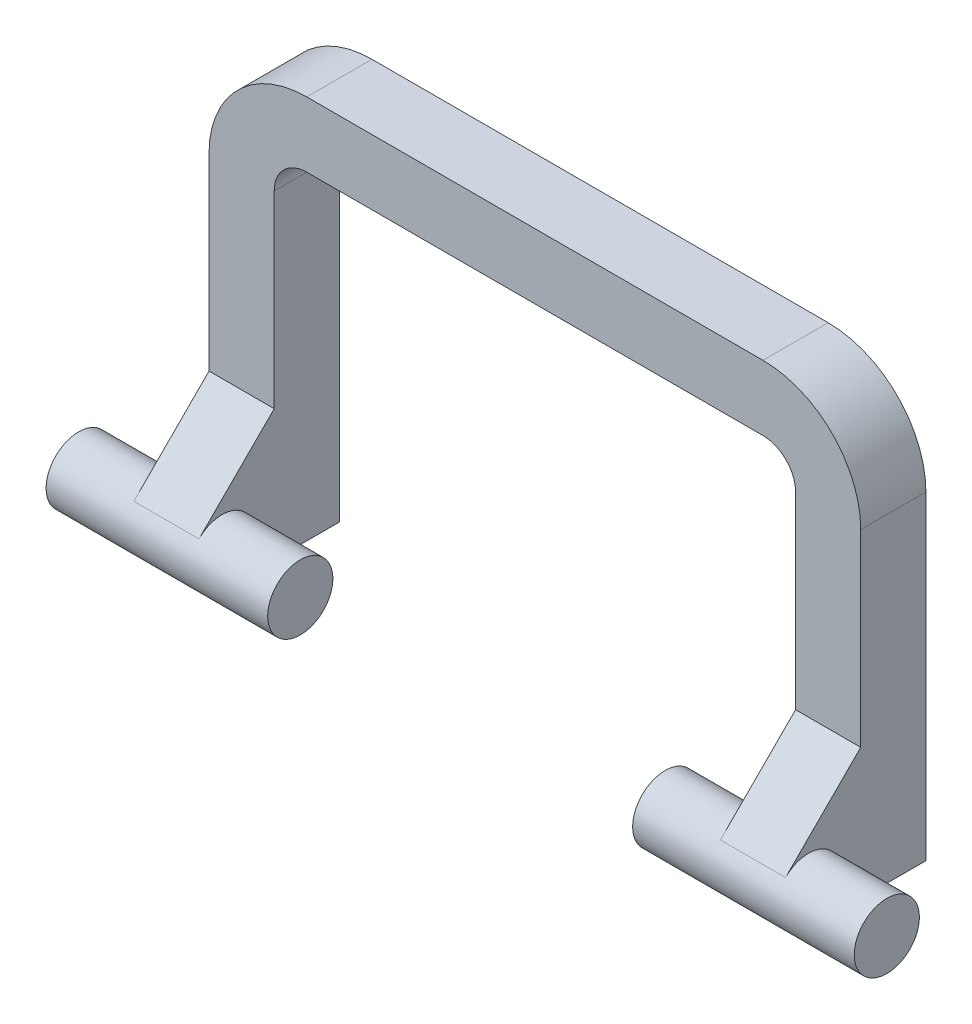
SolidWorks part; units mm, degrees
ref_plane "前视基准面" through (0, 0, 0) normal (0, 0, 1) x (1, 0, 0)
ref_plane "上视基准面" through (0, 0, 0) normal (0, 1, 0) x (1, 0, 0)
ref_plane "右视基准面" through (0, 0, 0) normal (1, 0, 0) x (0, 0, -1)
sketch "草图1" plane through (0, 0, 0) normal (0, 0, 1) x (1, 0, 0)
  line L1 (45, 0) -> (45, 59)
  line L2 (-45, 0) -> (-45, 59)
  line L3 (-45, 59) -> (45, 59)
  line L5 (0, 0) -> (45, 0) construction
  line L6 (0, 0) -> (-45, 0) construction
  point P4 (0, 0)
  dimension "D1" = 90
  dimension "D2" = 59
extrude "拉伸-薄壁1" add sketch "草图1" along normal blind 10 thin thin type mid plane wall 10
sketch "草图2" plane through (50, 0, 0) normal (1, 0, 0) x (0, 0, -1)
  line L4 (-10, 49) -> (-10, 0) construction
  line L6 (0, 49) -> (0, 0) construction
  line L7 (0, 17.0711) -> (0, 0)
  line L9 (-18, 0) -> (0, 0)
  line L11 (-21.5355, 8.5355) -> (-10, 20.0711)
  line L12 (-10, 20.0711) -> (0, 20.0711)
  line L13 (0, 20.0711) -> (0, 17.0711)
  arc A2 (-21.5355, 8.5355) -> (-18, 0) centre (-18, 5) ccw
extrude "凸台-拉伸1" add sketch "草图2" against normal blind 10
sketch "草图4" plane through (40, 0, 0) normal (-1, 0, 0) x (0, 0, 1)
  circle A0 centre (18, 5) radius 5
extrude "凸台-拉伸3" add sketch "草图4" along normal blind 12
mirror "镜向3" about plane through (0, 0, 0) normal (1, 0, 0) of "凸台-拉伸3", "凸台-拉伸1"
sketch "草图7" plane through (50, 0, 0) normal (1, 0, 0) x (0, 0, -1)
  line L0 (-18, 0) -> (0, 0) construction
  line L3 (-10, 49) -> (-10, 20.0711) construction
  circle A0 centre (-18, 5) radius 5
  dimension "D3" = 10
  dimension "D1" = 5
  dimension "D2" = 8
extrude "凸台-拉伸4" add sketch "草图7" along normal blind 12
mirror "镜向4" about plane through (0, 0, 0) normal (1, 0, 0) of "凸台-拉伸4"
